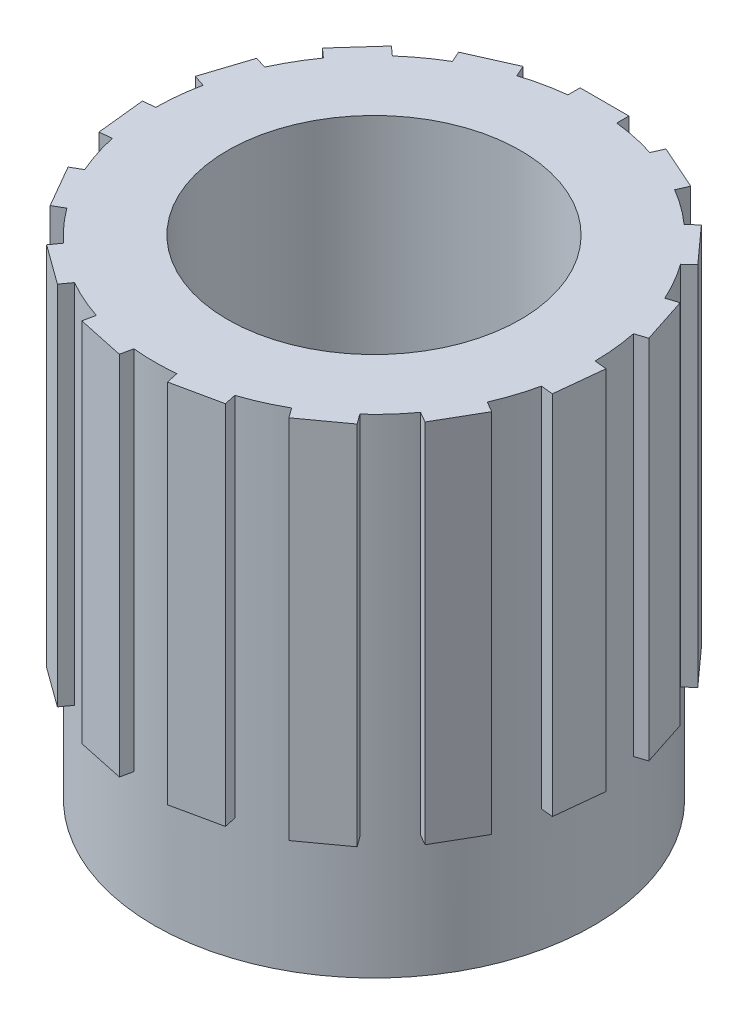
SolidWorks part; units mm, degrees
ref_plane "Front Plane" through (0, 0, 0) normal (0, 0, 1) x (1, 0, 0)
ref_plane "Top Plane" through (0, 0, 0) normal (0, 1, 0) x (1, 0, 0)
ref_plane "Right Plane" through (0, 0, 0) normal (1, 0, 0) x (0, 0, -1)
sketch "Sketch1" plane through (0, 0, 0) normal (0, 1, 0) x (1, 0, 0)
  circle A0 centre (0, 0) radius 1.8
  dimension "D1" = 3.6
extrude "Body" add sketch "Sketch1" along normal blind 4
sketch "Sketch2" plane through (0, 4, 0) normal (0, 1, 0) x (1, 0, 0)
  line L2 (-0.2, 1.7889) -> (-0.2, 1.8889)
  line L3 (-0.2, 1.8889) -> (0.2, 1.8889)
  line L4 (0.2, 1.7889) -> (0.2, 1.8889)
  circle A0 centre (0, 0) radius 1.8 construction
  arc A1 (0.2, 1.7889) -> (-0.2, 1.7889) centre (0, 0) ccw
  dimension "D1" = 0.1
  dimension "D2" = 0.2
  dimension "D3" = 0.4
extrude "Teeth" add sketch "Sketch2" against normal offset from surface (3 mm away) 1 up to face at (0, 0, 1.8)
pattern_circular "CirPattern1" count 15 over 360 about axis through (0, 0, 0) along (0, 1, 0) of "Teeth"
hole_wizard "M2 Clearance Hole1" positions "Sketch3" profile "Sketch4" hole size "M2" standard "ANSI Metric" end condition through all
sketch "Sketch3" plane through (0, 4, 0) normal (0, 1, 0) x (1, 0, 0)
  point P0 (0, 0)
sketch "Sketch4" plane through (0, 4, 0) normal (1, 0, 0) x (0, 0, 1)
  line L0 (0, 0) -> (0, 4)
  line L1 (0, 4) -> (1.2, 4)
  line L2 (1.2, 4) -> (1.2, 0)
  line L5 (1.2, 0) -> (0, 0)
  line L11 (0, -6.35) -> (0, 107.95) construction
  dimension "Thru Hole Dia." = 2.4
  dimension "Thru Hole Depth" = 4
